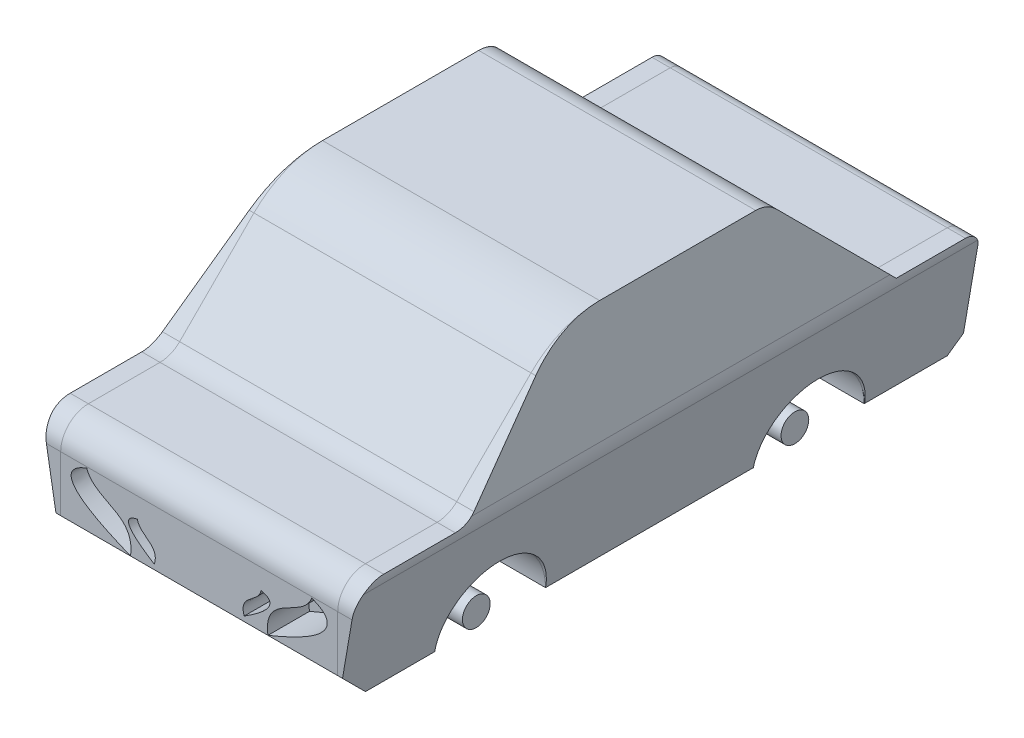
SolidWorks part; units mm, degrees
ref_plane "Front Plane" through (0, 0, 0) normal (0, 0, 1) x (1, 0, 0)
ref_plane "Top Plane" through (0, 0, 0) normal (0, 1, 0) x (1, 0, 0)
ref_plane "Right Plane" through (0, 0, 0) normal (1, 0, 0) x (0, 0, -1)
sketch "Car_Profile" plane through (0, 0, 0) normal (1, 0, 0) x (0, 0, -1)
  line L1 (2250, 0) -> (2250, 800)
  line L2 (2250, 800) -> (1650, 800)
  line L3 (1650, 800) -> (850, 1600)
  line L4 (850, 1600) -> (-650, 1600)
  line L5 (-650, 1600) -> (-1450, 800)
  line L6 (-1450, 800) -> (-2250, 800)
  line L7 (-2250, 800) -> (-2250, 0)
  line L11 (-2250, 0) -> (2250, 0)
  dimension "D1" = 4500
  dimension "D4" = 600
  dimension "D5" = 135
  dimension "D6" = 800
  dimension "D7" = 800
  dimension "D8" = 800
  dimension "D9" = 1500
extrude "Boss-Extrude1" add sketch "Car_Profile" along normal mid plane 2000
fillet "Fillet1" radius 700 1 edges at (0, 1600, 650)
fillet "Fillet2" radius 200 1 edges at (0, 1600, -850)
fillet "Fillet3" radius 200 1 edges at (0, 800, 1450)
fillet "Fillet4" radius 200 1 edges at (0, 800, 2250)
chamfer "Chamfer1" distance 200 angle 45 1 edges at (0, 0, 2250)
fillet "Fillet5" radius 100 1 edges at (0, 800, -2250)
chamfer "Chamfer2" distance 100 angle 45 1 edges at (0, 0, -2250)
sketch "Sketch3" plane through (0, 0, 2250) normal (0, 0, 1) x (1, 0, 0)
  line L0 (0, 0) -> (0, 600) construction
  line L9 (1000, 600) -> (-1000, 600) construction
  line L11 (-1000, 200) -> (1000, 200) construction
  spline S0 degree 3 poles (-812.2204, 592.0684) (-750.6712, 420.3143) (-457.5778, 466.7042) (-496.0566, 200) knots 0 0 0 0 1 1 1 1
  spline S1 degree 3 poles (-812.2204, 592.0684) (-1175.6025, 453.3603) (-543.3577, 223.4581) (-496.0566, 200) knots 0 0 0 0 1 1 1 1
  spline S2 degree 3 poles (-446.0965, 455.3261) (-637.0704, 418.576) (-345.7117, 250.4771) (-324.4572, 234.8194) knots 0 0 0 0 1 1 1 1
  spline S3 degree 3 poles (-446.0965, 455.3261) (-430.7018, 365.4097) (-282.3537, 362.8047) (-324.4572, 234.8194) knots 0 0 0 0 1 1 1 1
  spline S4 degree 3 poles (446.0965, 455.3261) (430.7018, 365.4097) (282.3537, 362.8047) (324.4572, 234.8194) knots 0 0 0 0 1 1 1 1
  spline S5 degree 3 poles (446.0965, 455.3261) (637.0704, 418.576) (345.7117, 250.4771) (324.4572, 234.8194) knots 0 0 0 0 1 1 1 1
  spline S6 degree 3 poles (812.2204, 592.0684) (1175.6025, 453.3603) (543.3577, 223.4581) (496.0566, 200) knots 0 0 0 0 1 1 1 1
  spline S7 degree 3 poles (812.2204, 592.0684) (750.6712, 420.3143) (457.5778, 466.7042) (496.0566, 200) knots 0 0 0 0 1 1 1 1
sketch "Sketch4" plane through (1000, 0, 0) normal (1, 0, 0) x (0, 0, -1)
  line L0 (-2050, 0) -> (2150, 0) construction
  line L1 (-750, 0) -> (-1550, 0)
  line L2 (750, 0) -> (1550, 0)
  arc A0 (-1550, 0) -> (-750, 0) centre (-1150, 0) cw
  arc A1 (1550, 0) -> (750, 0) centre (1150, 0) ccw
  dimension "D1" = 400
  dimension "D2" = 400
  dimension "D3" = 750
  dimension "D4" = 750
extrude "Cut-Extrude3" cut sketch "Sketch4" against normal blind 400
sketch "Sketch6" plane through (-1000, 0, 0) normal (-1, 0, 0) x (0, 0, 1)
  line L0 (2050, 0) -> (-2150, 0) construction
  line L1 (-750, 0) -> (-1550, 0)
  line L2 (750, 0) -> (1550, 0)
  arc A0 (-750, 0) -> (-1550, 0) centre (-1150, 0) ccw
  arc A1 (1550, 0) -> (750, 0) centre (1150, 0) ccw
  dimension "D1" = 400
  dimension "D2" = 400
  dimension "D3" = 750
  dimension "D4" = 750
extrude "Cut-Extrude4" cut sketch "Sketch6" against normal blind 400
sketch "Sketch7" plane through (0, 0, 0) normal (1, 0, 0) x (0, 0, -1)
  line L0 (-1550, 0) -> (-750, 0) construction
  line L1 (750, 0) -> (1550, 0) construction
  circle A0 centre (-1150, 0) radius 100
  circle A1 centre (1150, 0) radius 100
  dimension "D1" = 200
  dimension "D2" = 200
extrude "Boss-Extrude2" add sketch "Sketch7" along normal mid plane 1800
extrude "Cut-Extrude6" cut sketch "Sketch3" against normal blind 300 contours S2 S3 | S0 S1 | S4 S5 | S6 S7
sketch "Sketch8" plane through (0, 0, 2250) normal (0, 0, 1) x (1, 0, 0)
  line L0 (-1000, 0) -> (-1000, 1600)
  line L1 (-1000, 1600) -> (-1135.9007, 790.4828)
  line L2 (-1135.9007, 790.4828) -> (-1000, 0)
  line L3 (0, 0) -> (0, 1600) construction
  line L4 (-1000, 1600) -> (1000, 1600) construction
  line L5 (1000, 1600) -> (1135.9007, 790.4828)
  line L6 (1000, 0) -> (1000, 1600)
  line L7 (1135.9007, 790.4828) -> (1000, 0)
  point P13 (-1135.9007, 790.4828)
extrude "Boss-Extrude3" add sketch "Sketch8" against normal blind 4500 separate body
sketch "Sketch9" plane through (1000, 0, 0) normal (-1, 0, 0) x (0, 0, 1)
  line L0 (-2250, 700) -> (-2250, 1600)
  line L1 (-2250, 1600) -> (-767.1573, 1600)
  line L2 (-1650, 800) -> (-908.5786, 1541.4214)
  line L3 (-1650, 800) -> (-2150, 800)
  line L4 (-2150, 800) -> (-1650, 800) construction
  line L5 (2050, 800) -> (1532.8427, 800)
  line L6 (1391.4214, 858.5786) -> (855.0253, 1394.9747)
  line L7 (360.0505, 1600) -> (2250, 1600)
  line L8 (2250, 1600) -> (2250, 600)
  line L9 (2250, 200) -> (2050, 0)
  line L10 (2050, 0) -> (2250, 0)
  line L11 (2250, 0) -> (2250, 200)
  line L12 (-2250, 100) -> (-2250, 0)
  line L13 (-2250, 0) -> (-2150, 0)
  line L14 (-2150, 0) -> (-2250, 100)
  arc A0 (-767.1573, 1600) -> (-908.5786, 1541.4214) centre (-767.1573, 1400) ccw
  arc A1 (-2150, 800) -> (-2250, 700) centre (-2150, 700) ccw
  arc A2 (2050, 800) -> (2250, 600) centre (2050, 600) cw
  arc A3 (1532.8427, 800) -> (1391.4214, 858.5786) centre (1532.8427, 1000) cw
  arc A4 (855.0253, 1394.9747) -> (360.0505, 1600) centre (360.0505, 900) ccw
extrude "Cut-Extrude7" cut sketch "Sketch9" against normal through all both and the other way through all
fillet "Fillet6" radius 300 1 edges at (-1135.9007, 790.4828, -40.8081)
fillet "Fillet7" radius 300 1 edges at (1135.9007, 790.4828, -40.8081)
sketch "Sketch10" plane through (-1000, 0, 0) normal (1, 0, 0) x (0, 0, -1)
  line L0 (2150, 0) -> (-2050, 0) construction
  line L1 (-1550, 0) -> (-750, 0)
  line L2 (1550, 0) -> (750, 0)
  arc A0 (-750, 0) -> (-1550, 0) centre (-1150, 0) ccw
  arc A1 (1550, 0) -> (750, 0) centre (1150, 0) ccw
extrude "Cut-Extrude8" cut sketch "Sketch10" against normal through all
sketch "Sketch11" plane through (1000, 0, 0) normal (-1, 0, 0) x (0, 0, 1)
  line L0 (-2150, 0) -> (2050, 0) construction
  line L1 (1550, 0) -> (750, 0)
  line L2 (-750, 0) -> (-1553.8124, 0)
  arc A0 (1550, 0) -> (750, 0) centre (1150, 0) ccw
  arc A1 (1550, 0) -> (750, 0) centre (1150, 0) ccw construction
  arc A2 (-750, 0) -> (-1553.8124, 0) centre (-1151.9062, -14.6175) ccw
extrude "Cut-Extrude9" cut sketch "Sketch11" against normal through all
